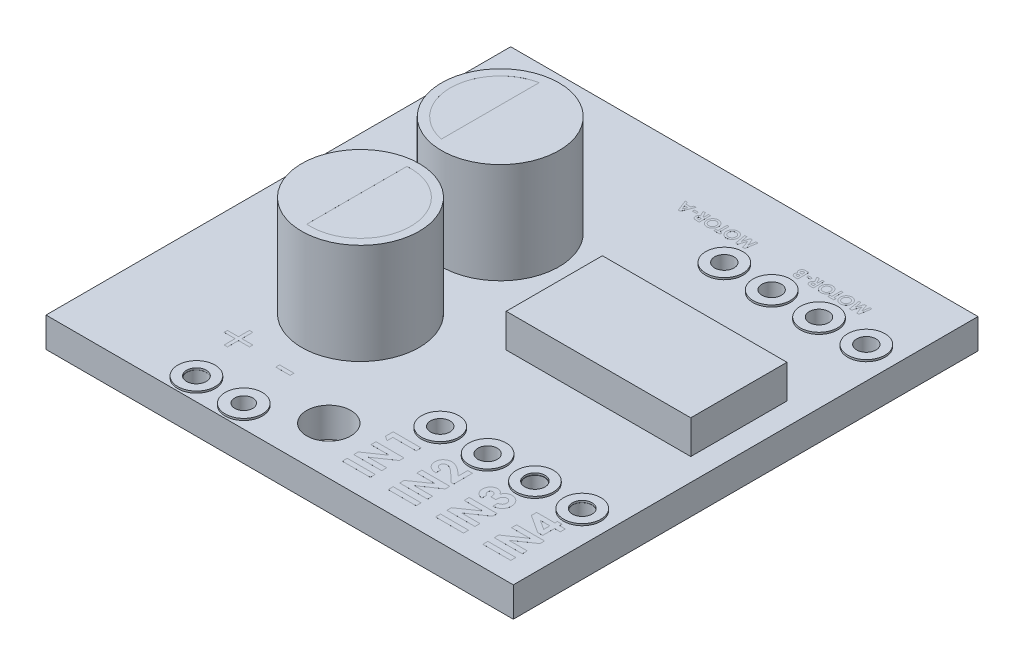
SolidWorks part; units mm, degrees
ref_plane "Front Plane" through (0, 0, 0) normal (0, 0, 1) x (1, 0, 0)
ref_plane "Top Plane" through (0, 0, 0) normal (0, 1, 0) x (1, 0, 0)
ref_plane "Right Plane" through (0, 0, 0) normal (1, 0, 0) x (0, 0, -1)
sketch "Sketch1" plane through (0, 0, 0) normal (0, 1, 0) x (1, 0, 0)
  line L1 (12.535, -12.465) -> (-12.535, -12.465)
  line L2 (12.535, -12.465) -> (12.535, 12.465)
  line L3 (12.535, 12.465) -> (-12.535, 12.465)
  line L4 (-12.535, -12.465) -> (-12.535, 12.465)
  line L5 (12.535, -12.465) -> (-12.535, 12.465) construction
  line L6 (12.535, 12.465) -> (-12.535, -12.465) construction
  point P0 (0, 0)
  dimension "D1" = 25.07
  dimension "D2" = 24.93
extrude "Boss-Extrude1" add sketch "Sketch1" along normal blind 1.6
sketch "Sketch2" plane through (0, 1.6, 0) normal (0, 1, 0) x (1, 0, 0)
  line L0 (12.535, -12.465) -> (12.535, 12.465) construction
  line L2 (-12.535, -12.465) -> (12.535, -12.465) construction
  circle A0 centre (10.935, 8.075) radius 0.52
  circle A1 centre (10.935, -7.165) radius 0.52
  circle A2 centre (5.855, -7.165) radius 0.52
  circle A3 centre (5.855, 8.075) radius 0.52
  circle A4 centre (-3.035, -11.355) radius 0.52
  dimension "D1" = 1.04
  dimension "D2" = 1.6
  dimension "D3" = 15.24
  dimension "D4" = 1.6
  dimension "D5" = 5.08
  dimension "D6" = 5.08
  dimension "D7" = 13.97
  dimension "D8" = 5.3
  dimension "D9" = 4.19
extrude "Cut-Extrude1" cut sketch "Sketch2" against normal blind 1.6
pattern_linear "LPattern1" count 2 spacing 2.54 along (-1, 0, 0) of "Cut-Extrude1"
sketch "Sketch3" plane through (0, 1.6, 0) normal (0, 1, 0) x (1, 0, 0)
  line L0 (12.535, -12.465) -> (12.535, 12.465) construction
  line L1 (11.335, -1.745) -> (1.435, -1.745)
  line L2 (11.335, -1.745) -> (11.335, 3.415)
  line L3 (11.335, 3.415) -> (1.435, 3.415)
  line L4 (1.435, -1.745) -> (1.435, 3.415)
  line L5 (11.335, -1.745) -> (1.435, 3.415) construction
  line L6 (11.335, 3.415) -> (1.435, -1.745) construction
  line L7 (-12.535, -12.465) -> (12.535, -12.465) construction
  point P0 (6.385, 0.835)
  dimension "D1" = 5.16
  dimension "D2" = 9.9
  dimension "D3" = 1.2
  dimension "D4" = 10.72
extrude "Boss-Extrude2" add sketch "Sketch3" along normal blind 1.8 separate body
sketch "Sketch4" plane through (0, 1.6, 0) normal (0, 1, 0) x (1, 0, 0)
  line L0 (-12.535, -12.465) -> (12.535, -12.465) construction
  line L1 (12.535, -12.465) -> (12.535, 12.465) construction
  circle A0 centre (-4.165, 3.535) radius 3.15
  circle A1 centre (-4.165, -3.965) radius 3.15
  dimension "D1" = 6.3
  dimension "D2" = 7.5
  dimension "D3" = 8.5
  dimension "D4" = 16.7
extrude "Boss-Extrude3" add sketch "Sketch4" along normal blind 5.4 separate body
sketch "Sketch5" plane through (0, 0, 0) normal (0, -1, 0) x (-1, 0, 0)
  line L1 (-11.26, 8.4) -> (-10.61, 8.4)
  line L2 (-11.26, 8.4) -> (-11.26, 7.75)
  line L3 (-11.26, 7.75) -> (-10.61, 7.75)
  line L4 (-10.61, 8.4) -> (-10.61, 7.75)
  line L5 (-11.26, 8.4) -> (-10.61, 7.75) construction
  line L6 (-11.26, 7.75) -> (-10.61, 8.4) construction
  line L7 (-6.18, 8.4) -> (-5.53, 8.4)
  line L8 (-6.18, 8.4) -> (-6.18, 7.75)
  line L9 (-6.18, 7.75) -> (-5.53, 7.75)
  line L10 (-5.53, 8.4) -> (-5.53, 7.75)
  line L11 (-6.18, 8.4) -> (-5.53, 7.75) construction
  line L12 (-6.18, 7.75) -> (-5.53, 8.4) construction
  line L13 (-11.26, -6.84) -> (-10.61, -6.84)
  line L14 (-11.26, -6.84) -> (-11.26, -7.49)
  line L15 (-11.26, -7.49) -> (-10.61, -7.49)
  line L16 (-10.61, -6.84) -> (-10.61, -7.49)
  line L17 (-11.26, -6.84) -> (-10.61, -7.49) construction
  line L18 (-11.26, -7.49) -> (-10.61, -6.84) construction
  line L19 (-6.18, -6.84) -> (-5.53, -6.84)
  line L20 (-6.18, -6.84) -> (-6.18, -7.49)
  line L21 (-6.18, -7.49) -> (-5.53, -7.49)
  line L22 (-5.53, -6.84) -> (-5.53, -7.49)
  line L23 (-6.18, -6.84) -> (-5.53, -7.49) construction
  line L24 (-6.18, -7.49) -> (-5.53, -6.84) construction
  line L25 (2.71, -11.03) -> (3.36, -11.03)
  line L26 (2.71, -11.03) -> (2.71, -11.68)
  line L27 (2.71, -11.68) -> (3.36, -11.68)
  line L28 (3.36, -11.03) -> (3.36, -11.68)
  line L29 (2.71, -11.03) -> (3.36, -11.68) construction
  line L30 (2.71, -11.68) -> (3.36, -11.03) construction
  point P0 (-10.935, 8.075)
  point P6 (-5.855, 8.075)
  point P12 (-10.935, -7.165)
  point P18 (-5.855, -7.165)
  point P24 (3.035, -11.355)
  dimension "D1" = 0.65
  dimension "D2" = 0.65
sketch "Sketch7" plane through (0, 1.6, 0) normal (0, 1, 0) x (1, 0, 0)
  line L0 (12.535, -12.465) -> (12.535, 12.465) construction
  line L1 (-12.535, -12.465) -> (12.535, -12.465) construction
  circle A0 centre (0.075, -9.905) radius 1.185
  dimension "D1" = 2.37
  dimension "D2" = 12.46
  dimension "D3" = 2.56
extrude "Cut-Extrude2" cut sketch "Sketch7" against normal blind 1.66
sketch "Sketch8" plane through (0, 7, 0) normal (0, 1, 0) x (1, 0, 0)
  line L0 (-4.7029, 6.1597) -> (-4.7029, 0.9103)
  line L2 (-4.3604, -1.2797) -> (-4.3604, -6.6503)
  arc A0 (-4.7029, 6.1597) -> (-4.7029, 0.9103) centre (-4.165, 3.535) ccw
  arc A1 (-4.3604, -6.6503) -> (-4.3604, -1.2797) centre (-4.165, -3.965) ccw
extrude "Cut-Extrude3" cut sketch "Sketch8" against normal blind 0.001
sketch "Sketch9" plane through (0, 1.6, 0) normal (0, 1, 0) x (1, 0, 0)
  line L0 (-7.826, -9.3876) -> (-2.146, -9.3876) construction
  text T0 " +  - " font "Century Gothic" height 2
extrude "Boss-Extrude4" add sketch "Sketch9" along normal blind 0.001
sketch "Sketch10" plane through (0, 1.6, 0) normal (0, 1, 0) x (1, 0, 0)
  line L0 (3.7034, -8.174) -> (3.7034, -11.9535) construction
  line L2 (6.255, -7.844) -> (6.255, -11.9535) construction
  line L4 (8.795, -7.844) -> (8.795, -11.9535) construction
  line L6 (11.335, -7.844) -> (11.335, -11.9535) construction
  circle A0 centre (3.315, -7.165) radius 0.52 construction
  circle A1 centre (5.855, -7.165) radius 0.52 construction
  circle A2 centre (8.395, -7.165) radius 0.52 construction
  circle A3 centre (10.935, -7.165) radius 0.52 construction
  text T0 "IN1" font "Century Gothic" height 1.5
  text T1 "IN2" font "Century Gothic" height 1.5
  text T2 "IN3" font "Century Gothic" height 1.5
  text T3 "IN4" font "Century Gothic" height 1.5
  dimension "D2" = 0.4
  dimension "D4" = 0.4
  dimension "D1" = 0.3884
  dimension "D3" = 0.4
extrude "Boss-Extrude5" add sketch "Sketch10" along normal blind 0.001
sketch "Sketch11" plane through (0, 1.6, 0) normal (0, 1, 0) x (1, 0, 0)
  line L0 (9.9779, 9.9725) -> (-1.3321, 9.9725) construction
  text T0 "MOTOR-B          MOTOR-A" font "Century Gothic" height 0.6
extrude "Boss-Extrude6" add sketch "Sketch11" along normal blind 0.001
sketch "Sketch12" plane through (0, 1.6, 0) normal (0, 1, 0) x (1, 0, 0)
  circle A0 centre (10.935, 8.075) radius 1
  circle A1 centre (8.395, 8.075) radius 1
  circle A2 centre (5.855, 8.075) radius 1
  circle A3 centre (3.315, 8.075) radius 1
  circle A4 centre (-5.575, -11.355) radius 1
  circle A5 centre (-3.035, -11.355) radius 1
  circle A6 centre (3.315, -7.165) radius 1
  circle A7 centre (5.855, -7.165) radius 1
  circle A8 centre (8.395, -7.165) radius 1
  circle A9 centre (10.935, -7.165) radius 1
  circle A10 centre (-5.575, -11.355) radius 0.5273
  circle A11 centre (-3.035, -11.355) radius 0.4847
  circle A12 centre (3.315, -7.165) radius 0.52
  circle A13 centre (5.855, -7.165) radius 0.52
  circle A14 centre (8.395, -7.165) radius 0.5429
  circle A15 centre (10.935, -7.165) radius 0.5286
  circle A16 centre (3.315, 8.075) radius 0.52
  circle A17 centre (5.855, 8.075) radius 0.52
  circle A18 centre (8.395, 8.075) radius 0.52
  circle A19 centre (10.935, 8.075) radius 0.52
  circle A20 centre (5.855, -7.165) radius 0.52 construction
  dimension "D1" = 2
extrude "Boss-Extrude7" add sketch "Sketch12" along normal blind 0.1 and the other way blind 1.7
